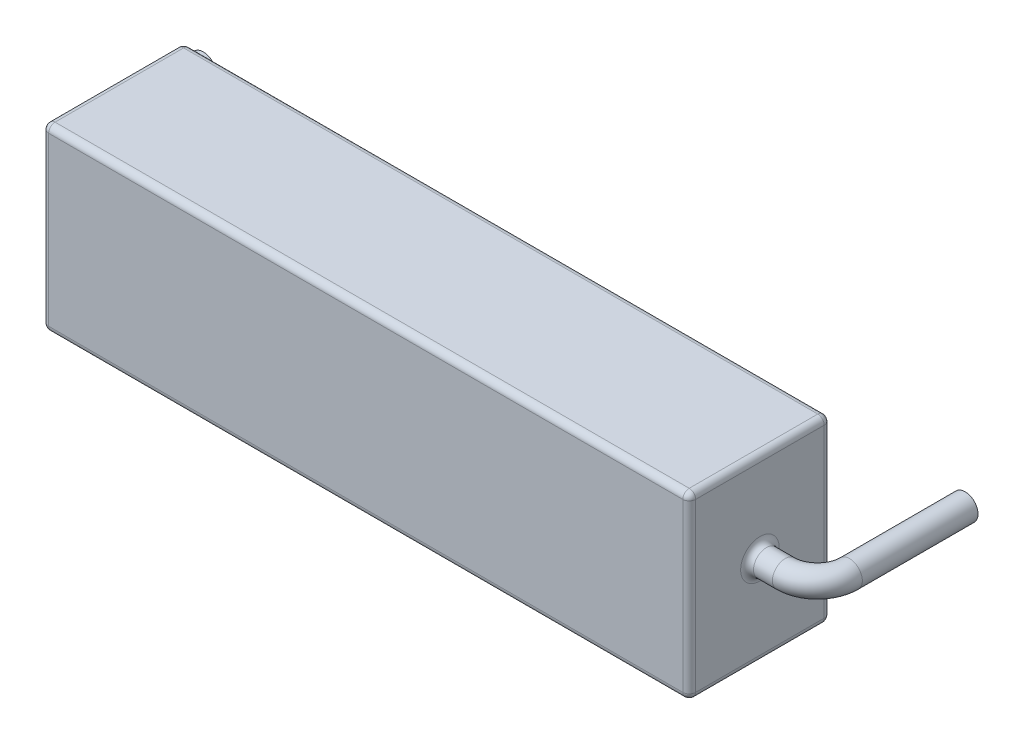
SolidWorks part; units mm, degrees
ref_plane "Front Plane" through (0, 0, 0) normal (0, 0, 1) x (1, 0, 0)
ref_plane "Top Plane" through (0, 0, 0) normal (0, 1, 0) x (1, 0, 0)
ref_plane "Right Plane" through (0, 0, 0) normal (1, 0, 0) x (0, 0, -1)
sketch "Sketch1" plane through (0, 0, 0) normal (0, 0, 1) x (1, 0, 0)
  line L1 (0, 0) -> (15.1, 0)
  line L2 (0, 0) -> (0, 4.2)
  line L3 (0, 4.2) -> (15.1, 4.2)
  line L4 (15.1, 0) -> (15.1, 4.2)
  dimension "D1" = 15.1
  dimension "D2" = 4.2
extrude "Boss-Extrude1" add sketch "Sketch1" along normal blind 3.3
ref_plane "Plane1" through (0, 2.1, 0) normal (0, 1, 0) x (1, 0, 0)
sketch "Sketch2" plane through (0, 2.1, 0) normal (0, 1, 0) x (1, 0, 0)
  line L0 (0, -1.65) -> (15.1, -1.65)
  line L1 (0, -3.3) -> (0, 0) construction
  line L2 (15.1, -3.3) -> (15.1, 0) construction
  line L3 (15.1, -1.65) -> (15.69, -1.65)
  line L4 (16.44, -0.9) -> (16.44, 1.8)
  line L5 (7.55, -3.3) -> (7.55, 0) construction
  line L6 (0, -3.3) -> (15.1, -3.3) construction
  line L7 (-1.34, 1.8) -> (-1.34, -0.9)
  line L8 (-0.59, -1.65) -> (0, -1.65)
  line L9 (0, 0) -> (15.1, 0) construction
  arc A0 (16.44, -0.9) -> (15.69, -1.65) centre (15.69, -0.9) cw
  arc A1 (-1.34, -0.9) -> (-0.59, -1.65) centre (-0.59, -0.9) ccw
  dimension "D2" = 0.75
  dimension "D1" = 17.78
  dimension "D3" = 1.8
ref_plane "Plane2" through (0, 0, -1.8) normal (0, 0, 1) x (1, 0, 0)
sketch "Sketch5" plane through (0, 0, -1.8) normal (0, 0, 1) x (1, 0, 0)
  circle A0 centre (-1.34, 2.1) radius 0.3
  dimension "D1" = 0.6
sweep "Sweep3" add profiles "Sketch5" path "Sketch2"
fillet "Fillet1" radius 0.15 14 edges at (15.1, 2.1, 3.3) (7.55, 4.2, 3.3) (0, 2.1, 1.35) (15.1, 2.1, 1.95) (0, 2.1, 3.3) (7.55, 4.2, 0) (15.1, 2.1, 0) (7.55, 0, 0) (0, 2.1, 0) (7.55, 0, 3.3) (0, 4.2, 1.65) (15.1, 4.2, 1.65) (15.1, 0, 1.65) (0, 0, 1.65)
